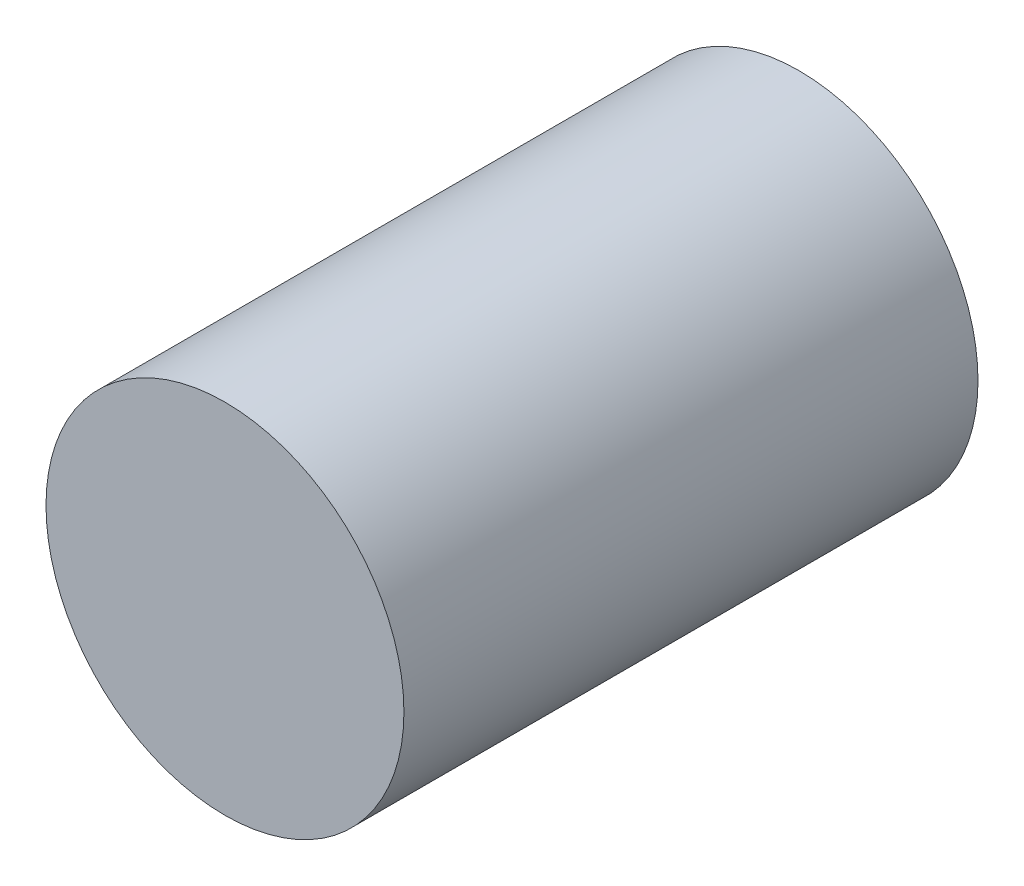
SolidWorks part; units mm, degrees
ref_plane "前视基准面" through (0, 0, 0) normal (0, 0, 1) x (1, 0, 0)
ref_plane "上视基准面" through (0, 0, 0) normal (0, 1, 0) x (1, 0, 0)
ref_plane "右视基准面" through (0, 0, 0) normal (1, 0, 0) x (0, 0, -1)
sketch "草图1" plane through (0, 0, 0) normal (0, 0, 1) x (1, 0, 0)
  circle A0 centre (-1, 0) radius 0.3117
extrude "凸台-拉伸1" add sketch "草图1" along normal mid plane 1
